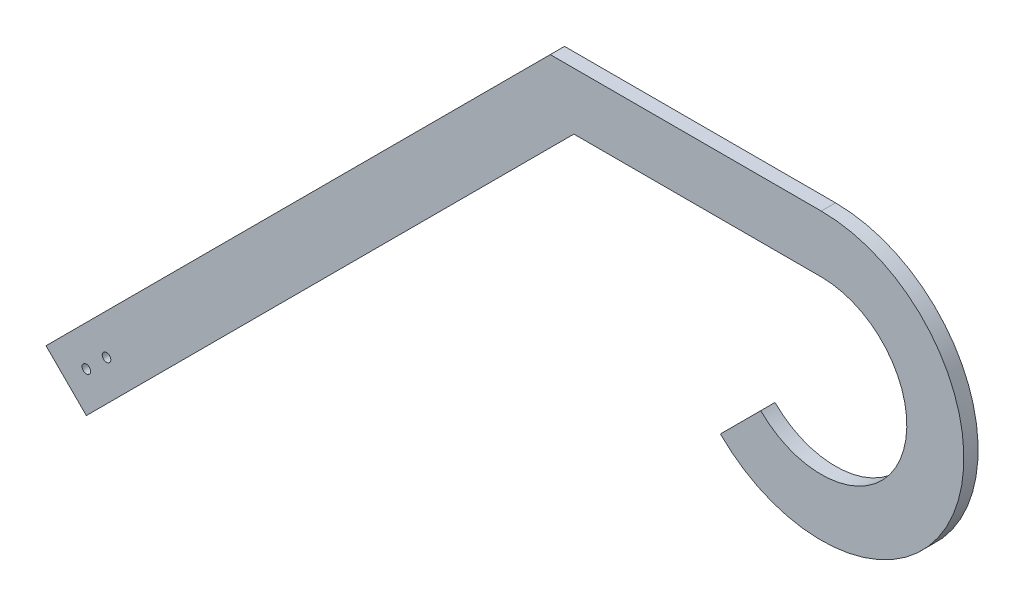
SolidWorks part; units mm, degrees
material "冷拉钢丝 45"
ref_plane "前视基准面" through (0, 0, 0) normal (0, 0, 1) x (1, 0, 0)
ref_plane "上视基准面" through (0, 0, 0) normal (0, 1, 0) x (1, 0, 0)
ref_plane "右视基准面" through (0, 0, 0) normal (1, 0, 0) x (0, 0, -1)
sketch "草图1" plane through (0, 0, 0) normal (0, 0, 1) x (1, 0, 0)
  line L0 (0, 50) -> (-95, 50)
  line L1 (-95, 50) -> (-271.7767, -126.7767)
  line L2 (-271.7767, -126.7767) -> (-257.6346, -140.9188)
  line L3 (0, 30) -> (-86.7157, 30)
  line L4 (-86.7157, 30) -> (-257.6346, -140.9188)
  line L5 (-21.2132, -21.2132) -> (-35.3553, -35.3553)
  arc A0 (-35.3553, -35.3553) -> (0, 50) centre (0, 0) ccw
  arc A1 (-21.2132, -21.2132) -> (0, 30) centre (0, 0) ccw
  point P3 (-245.6931, -3.6112)
  point P8 (-232.2976, -19.5827)
  dimension "D1" = 100
  dimension "D3" = 95
  dimension "D4" = 250
  dimension "D5" = 135
  dimension "D7" = 45
  dimension "D6" = 20
extrude "凸台-拉伸1" add sketch "草图1" along normal blind 5
sketch "草图2" plane through (0, 0, 5) normal (0, 0, 1) x (1, 0, 0)
  line L0 (-264.7056, -133.8478) -> (-238.5328, -107.6749) construction
  line L1 (-271.7767, -126.7767) -> (-257.6346, -140.9188) construction
  circle A0 centre (-257.6346, -126.7767) radius 1.5
  circle A1 centre (-250.5635, -119.7056) radius 1.5
  dimension "D1" = 3
  dimension "D2" = 3
  dimension "D3" = 10
  dimension "D4" = 10
extrude "切除-拉伸1" cut sketch "草图2" against normal through all
